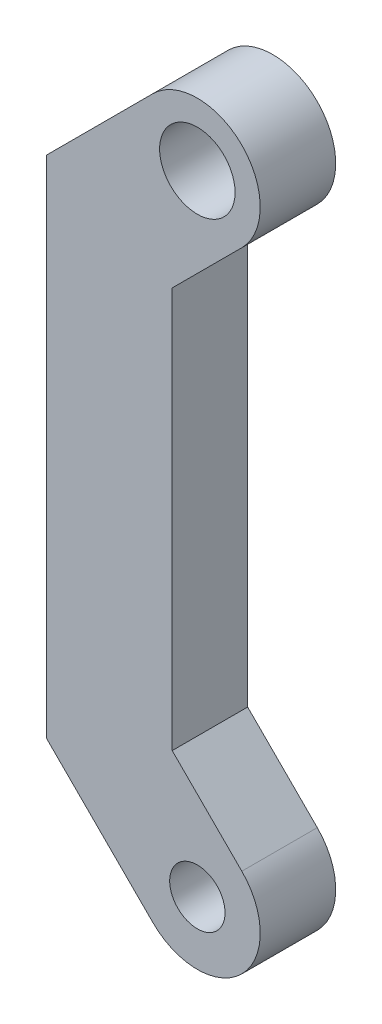
SolidWorks part; units mm, degrees
ref_plane "Alzado" through (0, 0, 0) normal (0, 0, 1) x (1, 0, 0)
ref_plane "Planta" through (0, 0, 0) normal (0, 1, 0) x (1, 0, 0)
ref_plane "Vista lateral" through (0, 0, 0) normal (1, 0, 0) x (0, 0, -1)
sketch "Croquis1" plane through (0, 0, 0) normal (0, 0, 1) x (1, 0, 0)
  line L0 (0, 0) -> (0, 25) construction
  line L1 (0, 0) -> (-3.5, 3.5) construction
  line L2 (-3.5, 3.5) -> (-3.5, 21.5) construction
  line L3 (-3.5, 21.5) -> (0, 25) construction
  line L4 (1.7678, 1.7678) -> (-1, 4.5355)
  line L5 (-1, 4.5355) -> (-1, 20.4645)
  line L6 (-1, 20.4645) -> (1.7678, 23.2322)
  line L7 (-1.7678, -1.7678) -> (-6, 2.4645)
  line L8 (-6, 2.4645) -> (-6, 22.5355)
  line L9 (-6, 22.5355) -> (-1.7678, 26.7678)
  circle A0 centre (0, 0) radius 1.1
  circle A1 centre (0, 0) radius 2.5
  circle A4 centre (0, 25) radius 1.5
  circle A5 centre (0, 25) radius 2.5
  dimension "D1" = 2.2
  dimension "D2" = 5
  dimension "D3" = 3
  dimension "D4" = 5
  dimension "D5" = 25
  dimension "D6" = 45
  dimension "D7" = 45
  dimension "D8" = 18
  dimension "D9" = 2.5
  dimension "D10" = 2.5
extrude "Saliente-Extruir1" add sketch "Croquis1" along normal blind 3 contours A5 L9 L8 L7 A1 L4 L5 L6 | A5 A4 | A1 A0
